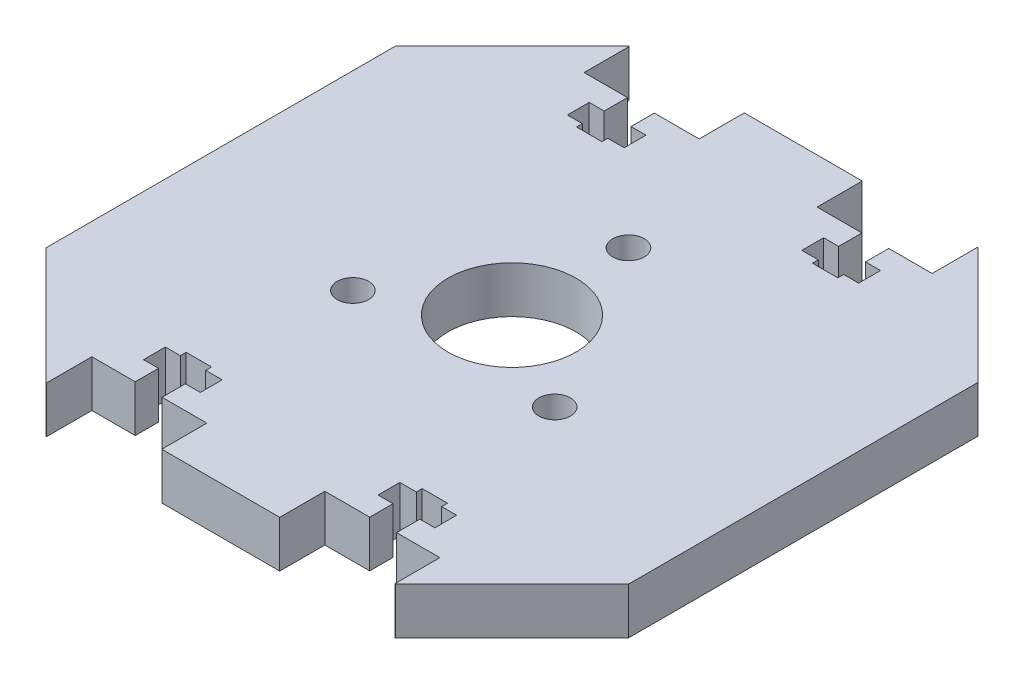
SolidWorks part; units mm, degrees
ref_plane "Front Plane" through (0, 0, 0) normal (0, 0, 1) x (1, 0, 0)
ref_plane "Top Plane" through (0, 0, 0) normal (0, 1, 0) x (1, 0, 0)
ref_plane "Right Plane" through (0, 0, 0) normal (1, 0, 0) x (0, 0, -1)
sketch "Sketch1" plane through (0, 0, 0) normal (0, 1, 0) x (1, 0, 0)
  line L0 (0, 15.875) -> (0, 8.7312) construction
  line L1 (-39.6875, 39.6875) -> (39.6875, 39.6875)
  line L2 (-39.6875, 39.6875) -> (-39.6875, -39.6875)
  line L3 (-39.6875, -39.6875) -> (39.6875, -39.6875)
  line L4 (39.6875, 39.6875) -> (39.6875, -39.6875)
  line L5 (-39.6875, 39.6875) -> (39.6875, -39.6875) construction
  line L6 (-39.6875, -39.6875) -> (39.6875, 39.6875) construction
  line L7 (-39.6875, 23.8125) -> (-23.8125, 39.6875)
  line L8 (-39.6875, -23.8125) -> (-23.8125, -39.6875)
  line L9 (0, 39.6875) -> (0, -39.6875) construction
  line L10 (39.6875, -23.8125) -> (23.8125, -39.6875)
  line L11 (39.6875, 23.8125) -> (23.8125, 39.6875)
  line L12 (-31.75, 39.6875) -> (-31.75, -39.6875) construction
  circle A0 centre (0, 0) radius 8.7312
  circle A1 centre (0, 15.875) radius 2.1526
  circle A2 centre (13.7482, -7.9375) radius 2.1527
  circle A3 centre (-13.7482, -7.9375) radius 2.1526
  circle A4 centre (-39.6875, 0) radius 23.8125
  point P16 (0, 0)
  dimension "D1" = 17.4625
  dimension "D2" = 4.3053
  dimension "D3" = 15.875
  dimension "D5" = 3
  dimension "D7" = 47.625
  dimension "D4" = 7.9375
  dimension "D6" = 7.1438
  dimension "D8" = 31.75
  dimension "D9" = 45
  dimension "D10" = 79.375
extrude "Boss-Extrude1" add sketch "Sketch1" along normal blind 6.35 contours A4 L8 L3 L10 L4 L11 L1 L7 A3 A2 A1 A0 | L2 A4 A3
sketch "Sketch2" plane through (0, 6.35, 0) normal (0, 1, 0) x (1, 0, 0)
  line L0 (-23.7125, -39.6875) -> (-8.0375, -39.6875)
  line L1 (-23.8125, -39.6875) -> (23.8125, -39.6875) construction
  line L2 (-23.7125, -39.6875) -> (-23.7125, -33.5375)
  line L3 (-23.7125, -33.5375) -> (-17.8038, -33.5375)
  line L4 (-8.0375, -33.5375) -> (-8.0375, -39.6875)
  line L5 (-8.0375, -39.6875) -> (8.0375, -39.6875)
  line L6 (19.8438, -30.3625) -> (19.8438, -27.3875)
  line L7 (19.8438, -27.3875) -> (17.8038, -27.3875)
  line L8 (17.8038, -27.3875) -> (17.8038, -26.5937)
  line L9 (17.8038, -26.5937) -> (14.3462, -26.5937)
  line L10 (-17.8038, -33.5375) -> (-17.8038, -30.3625)
  line L11 (-14.1462, -33.5375) -> (-14.1462, -30.3625)
  line L12 (-15.975, -33.3375) -> (-15.975, -27.3875) construction
  line L13 (-17.8038, -30.3625) -> (-19.8437, -30.3625)
  line L14 (-19.8437, -30.3625) -> (-19.8437, -27.3875)
  line L15 (-19.8437, -27.3875) -> (-17.8038, -27.3875)
  line L16 (-12.1062, -27.3875) -> (-12.1062, -30.3625)
  line L17 (-12.1062, -30.3625) -> (-14.1462, -30.3625)
  line L18 (-17.8038, -27.3875) -> (-17.8038, -26.5938)
  line L19 (-17.8038, -26.5938) -> (-14.3462, -26.5938)
  line L20 (-14.3462, -26.5938) -> (-14.3462, -27.3875)
  line L21 (-14.3462, -27.3875) -> (-12.1062, -27.3875)
  line L22 (-14.1462, -33.5375) -> (-8.0375, -33.5375)
  line L23 (0, -39.6875) -> (0, 39.6875) construction
  line L24 (-23.8125, -41.9227) -> (-7.9375, -41.9227) construction
  line L26 (-39.6875, 0) -> (39.6875, 0) construction
  line L27 (-39.6875, 23.8125) -> (-39.6875, -23.8125) construction
  line L28 (39.6875, 23.8125) -> (39.6875, -23.8125) construction
  line L29 (14.3462, -26.5937) -> (14.3462, -27.3875)
  line L30 (14.3462, -27.3875) -> (12.1063, -27.3875)
  line L31 (12.1063, -27.3875) -> (12.1063, -30.3625)
  line L32 (12.1063, -30.3625) -> (14.1462, -30.3625)
  line L33 (17.8038, -30.3625) -> (19.8438, -30.3625)
  line L34 (23.7125, -33.5375) -> (17.8038, -33.5375)
  line L35 (17.8038, -33.5375) -> (17.8038, -30.3625)
  line L36 (14.1462, -33.5375) -> (14.1462, -30.3625)
  line L37 (15.975, -33.3375) -> (15.975, -27.3875) construction
  line L38 (14.1462, -33.5375) -> (8.0375, -33.5375)
  line L39 (8.0375, -33.5375) -> (8.0375, -39.6875)
  line L40 (23.7125, -39.6875) -> (23.7125, -33.5375)
  line L41 (23.7125, -39.6875) -> (8.0375, -39.6875)
  line L42 (-23.7125, 39.6875) -> (-8.0375, 39.6875)
  line L43 (23.7125, 39.6875) -> (8.0375, 39.6875)
  line L44 (23.7125, 39.6875) -> (23.7125, 33.5375)
  line L45 (8.0375, 33.5375) -> (8.0375, 39.6875)
  line L46 (15.975, 33.3375) -> (15.975, 27.3875) construction
  line L47 (14.1462, 33.5375) -> (8.0375, 33.5375)
  line L48 (14.1462, 33.5375) -> (14.1462, 30.3625)
  line L49 (17.8038, 33.5375) -> (17.8038, 30.3625)
  line L50 (23.7125, 33.5375) -> (17.8038, 33.5375)
  line L51 (17.8038, 30.3625) -> (19.8438, 30.3625)
  line L52 (12.1063, 30.3625) -> (14.1462, 30.3625)
  line L53 (12.1063, 27.3875) -> (12.1063, 30.3625)
  line L54 (14.3462, 27.3875) -> (12.1063, 27.3875)
  line L55 (14.3462, 26.5937) -> (14.3462, 27.3875)
  line L56 (17.8038, 26.5937) -> (14.3462, 26.5937)
  line L57 (17.8038, 27.3875) -> (17.8038, 26.5937)
  line L58 (19.8438, 27.3875) -> (17.8038, 27.3875)
  line L59 (19.8438, 30.3625) -> (19.8438, 27.3875)
  line L60 (-15.975, 33.3375) -> (-15.975, 27.3875) construction
  line L61 (-14.1462, 33.5375) -> (-8.0375, 33.5375)
  line L62 (-14.3462, 27.3875) -> (-12.1062, 27.3875)
  line L63 (-14.3462, 26.5937) -> (-14.3462, 27.3875)
  line L64 (-17.8038, 26.5937) -> (-14.3462, 26.5937)
  line L65 (-17.8038, 27.3875) -> (-17.8038, 26.5937)
  line L66 (-12.1062, 30.3625) -> (-14.1462, 30.3625)
  line L67 (-12.1062, 27.3875) -> (-12.1062, 30.3625)
  line L68 (-19.8437, 27.3875) -> (-17.8038, 27.3875)
  line L69 (-19.8437, 30.3625) -> (-19.8437, 27.3875)
  line L70 (-17.8038, 30.3625) -> (-19.8437, 30.3625)
  line L71 (-14.1462, 33.5375) -> (-14.1462, 30.3625)
  line L72 (-17.8038, 33.5375) -> (-17.8038, 30.3625)
  line L73 (-8.0375, 33.5375) -> (-8.0375, 39.6875)
  line L74 (-23.7125, 33.5375) -> (-17.8038, 33.5375)
  line L75 (-23.7125, 39.6875) -> (-23.7125, 33.5375)
  point P85 (-15.875, -39.6875)
  point P88 (-15.875, -41.9227)
  line M28 (-23.8125, -39.6875) -> (23.8125, -39.6875)
  line M32 (23.8125, 39.6875) -> (-23.8125, 39.6875)
  dimension "D1" = 15.875
  dimension "D2" = 15.675
  dimension "D3" = 6.15
  dimension "D4" = 3.6576
  dimension "D5" = 3.175
  dimension "D6" = 2.975
  dimension "D7" = 7.7375
  dimension "D8" = 0.7937
  dimension "D9" = 3.4576
extrude "Cut-Extrude1" cut sketch "Sketch2" against normal through all contours L75 L74 L72 L70 L69 L68 L65 L64 L63 L62 L67 L66 L71 L61 L73 M32 | L59 L51 L49 L50 L44 L45 L47 L48 L52 L53 L54 L55 L56 L57 L58 M32 | L22 L11 L17 L16 L21 L20 L19 L18 L15 L14 L13 L10 L3 L2 L4 M28 | L40 L34 L35 L33 L6 L7 L8 L9 L29 L30 L31 L32 L36 L38 L39 M28
